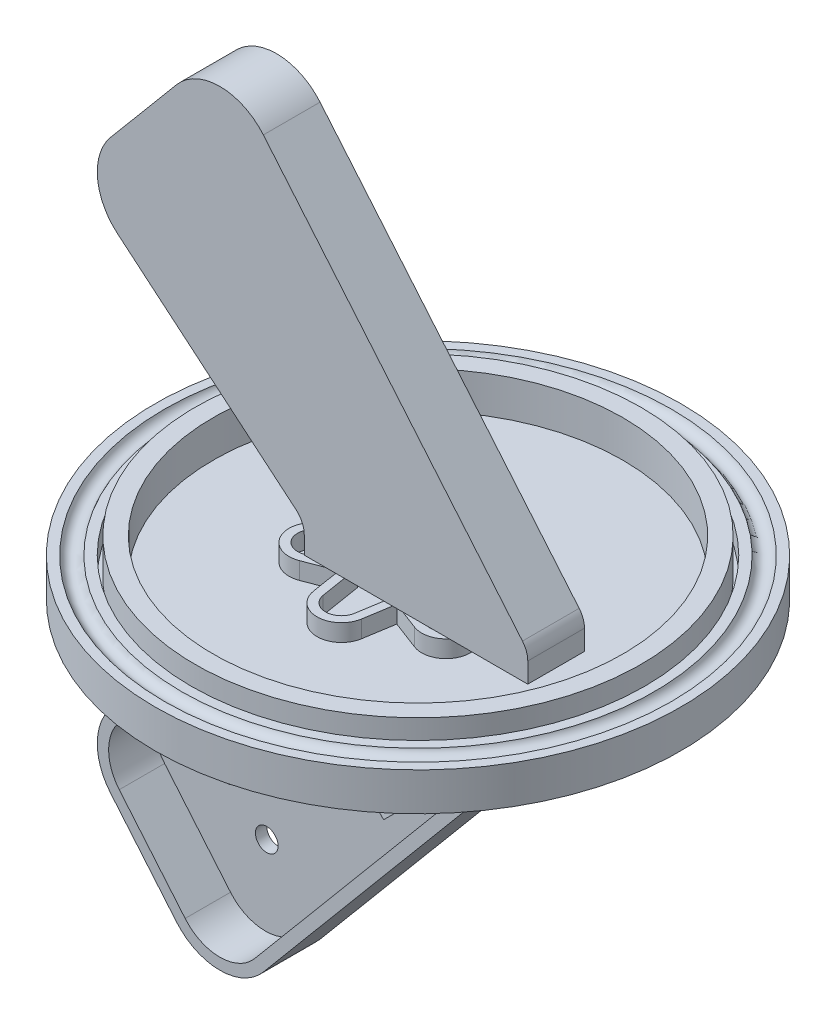
SolidWorks part; units mm, degrees
ref_plane "Front Plane" through (0, 0, 0) normal (0, 0, 1) x (1, 0, 0)
ref_plane "Top Plane" through (0, 0, 0) normal (0, 1, 0) x (1, 0, 0)
ref_plane "Right Plane" through (0, 0, 0) normal (1, 0, 0) x (0, 0, -1)
sketch "Sketch1" plane through (0, 0, 0) normal (0, 1, 0) x (1, 0, 0)
  circle A0 centre (0, 0) radius 82.55
  dimension "D1" = 165.1
extrude "Boss-Extrude1" add sketch "Sketch1" along normal blind 3.175 contours A0
sketch "Sketch3" plane through (0, 3.175, 0) normal (0, 1, 0) x (1, 0, 0)
  line L0 (0, 0) -> (-82.55, 0) construction
  circle A0 centre (0, 0) radius 82.55 construction
  circle A1 centre (-76.2, 0) radius 1.65
  dimension "D2" = 3.3
  dimension "D3" = 76.2
  dimension "D1" = 82.55
extrude "Cut-Extrude2" cut sketch "Sketch3" against normal blind 3.175
pattern_circular "CirPattern1" count 4 over 360 about axis through (0, 0, 0) along (0, 1, 0) of "Cut-Extrude2"
sketch "Sketch4" plane through (0, 3.175, 0) normal (0, 1, 0) x (1, 0, 0)
  line L0 (0, 0) -> (-9.65, 0) construction
  circle A0 centre (-9.65, 0) radius 40
  circle A1 centre (-9.65, 0) radius 46.35
  dimension "D2" = 6.35
  dimension "D3" = 80
  dimension "D1" = 9.65
extrude "Boss-Extrude2" add sketch "Sketch4" along normal blind 3.525
sketch "Sketch7" plane through (0, 0, 0) normal (0, 0, 1) x (1, 0, 0)
  line L1 (-9.65, 3.175) -> (-9.65, 34.2214) construction
  line L2 (82.55, 3.175) -> (-82.55, 3.175) construction
  circle A0 centre (-52.825, 7.2) radius 1.5875
  dimension "D1" = 3.175
  dimension "D2" = 52.825
  dimension "D3" = 4.025
revolve "Cut-Revolve1" cut sketch "Sketch7" angle 360 about L1
sketch "Sketch8" plane through (0, 3.175, 0) normal (0, 1, 0) x (1, 0, 0)
  circle A0 centre (-9.65, 0) radius 46.35
  circle A1 centre (-9.65, 0) radius 111.4897
extrude "Cut-Extrude3" cut sketch "Sketch8" against normal blind 10
sketch "Sketch12" plane through (0, 0, 0) normal (0, 0, 1) x (1, 0, 0)
  line L0 (-19.7064, 6.7) -> (-19.7064, 9.8348)
  line L1 (36.7, 6.7) -> (-56, 6.7) construction
  line L2 (-21.1352, 12.8989) -> (-52.6332, 39.3289)
  line L3 (-53.8657, 53.4172) -> (-42.2426, 67.2691)
  line L4 (-26.9217, 67.2691) -> (18.7706, 12.8153)
  line L5 (19.7064, 10.2441) -> (19.7064, 6.7)
  line L6 (-19.7064, 6.7) -> (19.7064, 6.7)
  line L7 (-56, 0) -> (36.7, 0) construction
  line L8 (0, 0) -> (0, 6.7) construction
  line L9 (30.35, 6.7) -> (-49.65, 6.7) construction
  line L10 (-19.7064, 11.7) -> (19.7064, 11.7) construction
  line L11 (-19.7064, 11.7) -> (19.7064, 6.7) construction
  line L12 (-19.7064, 6.7) -> (19.7064, 11.7) construction
  line L13 (0, 6.7) -> (0, 9.2) construction
  line L14 (-56, 0) -> (-56, 6.7) construction
  arc A0 (-52.6332, 39.3289) -> (-53.8657, 53.4172) centre (-46.2053, 46.9893) cw
  arc A1 (-42.2426, 67.2691) -> (-26.9217, 67.2691) centre (-34.5821, 60.8413) cw
  arc A2 (18.7706, 12.8153) -> (19.7064, 10.2441) centre (15.7064, 10.2441) cw
  arc A3 (-19.7064, 9.8348) -> (-21.1352, 12.8989) centre (-23.7064, 9.8348) ccw
  point P19 (-60.2936, 45.7567)
  point P22 (-34.5821, 76.3985)
  dimension "D6" = 10
  dimension "D7" = 4
  dimension "D1" = 40
  dimension "D2" = 50
  dimension "D3" = 40
  dimension "D4" = 80
  dimension "D5" = 5
extrude "Boss-Extrude4" add sketch "Sketch12" along normal blind 10 separate body contours L4 A2 L5 L6 L0 A3 L2 A0 L3 A1
ref_plane "Plane1" through (0, 3.35, 0) normal (0, 1, 0) x (1, 0, 0)
mirror "Mirror3" about plane through (0, 3.35, 0) normal (0, 1, 0) of "Boss-Extrude4"
sketch "Sketch13" plane through (0, 0, 10) normal (0, 0, 1) x (1, 0, 0)
  line L12 (-28.4538, -59.2836) -> (17.2385, -4.8297)
  line L13 (17.7064, -3.5441) -> (17.7064, -2)
  line L14 (17.7064, -2) -> (-17.7064, -2)
  line L15 (-17.7064, -2) -> (-17.7064, -3.1348)
  line L16 (-19.8497, -7.731) -> (-51.3476, -34.1609)
  line L17 (-52.3337, -45.4316) -> (-40.7105, -59.2836)
  line L18 (-28.4538, -59.2836) -> (17.2385, -4.8297)
  line L19 (17.7064, -3.5441) -> (17.7064, -2)
  line L20 (17.7064, -2) -> (-17.7064, -2)
  line L21 (-17.7064, -2) -> (-17.7064, -3.1348)
  line L22 (-19.8497, -7.731) -> (-51.3476, -34.1609)
  line L23 (-52.3337, -45.4316) -> (-40.7105, -59.2836)
  arc A8 (-40.7105, -59.2836) -> (-28.4538, -59.2836) centre (-34.5821, -54.1413) ccw
  arc A9 (17.2385, -4.8297) -> (17.7064, -3.5441) centre (15.7064, -3.5441) ccw
  arc A10 (-19.8497, -7.731) -> (-17.7064, -3.1348) centre (-23.7064, -3.1348) ccw
  arc A11 (-51.3476, -34.1609) -> (-52.3337, -45.4316) centre (-46.2053, -40.2893) ccw
  arc A12 (-40.7105, -59.2836) -> (-28.4538, -59.2836) centre (-34.5821, -54.1413) ccw
  arc A13 (17.2385, -4.8297) -> (17.7064, -3.5441) centre (15.7064, -3.5441) ccw
  arc A14 (-19.8497, -7.731) -> (-17.7064, -3.1348) centre (-23.7064, -3.1348) ccw
  arc A15 (-51.3476, -34.1609) -> (-52.3337, -45.4316) centre (-46.2053, -40.2893) ccw
  dimension "D1" = 2
extrude "Cut-Extrude4" cut sketch "Sketch13" against normal offset from surface (8 mm away) 2 up to face at (-18.0379, -22.3035, 0)
sketch "Sketch14" plane through (0, 0, 2) normal (0, 0, 1) x (1, 0, 0)
  line L0 (-42.2028, -34.4964) -> (-13.7064, -6) construction
  line L1 (-13.7064, -6) -> (0.6479, -20.3543)
  line L2 (0.6479, -20.3543) -> (-27.8485, -48.8507) construction
  line L3 (-27.8485, -48.8507) -> (-42.2028, -34.4964) construction
  line L4 (-56, 0) -> (36.7, 0) construction
  line L5 (17.7064, -2) -> (-17.7064, -2) construction
  line L7 (-19.7064, 0) -> (-19.7064, -3.1348) construction
  line L8 (-41.3896, -40.9664) -> (-7.2364, -6.8132) construction
  line L9 (-7.2364, -6.8132) -> (-0.1653, -13.8842) construction
  line L10 (-0.1653, -13.8842) -> (-34.3185, -48.0375) construction
  line L11 (-34.3185, -48.0375) -> (-41.3896, -40.9664) construction
  line L12 (-37.8541, -44.502) -> (-35.0257, -41.6735) construction
  line L13 (-24.313, -23.8898) -> (-27.9546, -20.2482) construction
  line L14 (-28.0607, -20.3543) -> (-13.7064, -34.7085)
  line L15 (-13.7064, -34.7085) -> (0.6479, -20.3543)
  line L16 (-13.7064, -6) -> (-28.0607, -20.3543)
  circle A0 centre (-7.2364, -6.8132) radius 2
  circle A1 centre (-0.1653, -13.8842) radius 2
  circle A2 centre (-41.3896, -40.9664) radius 2
  circle A3 centre (-34.3185, -48.0375) radius 2
  dimension "D6" = 4
  dimension "D1" = 45
  dimension "D2" = 4
  dimension "D3" = 40.3
  dimension "D4" = 20.3
  dimension "D5" = 6
  dimension "D7" = 10
  dimension "D8" = 48.3
  dimension "D9" = 20
extrude "Cut-Extrude5" cut sketch "Sketch14" against normal up to next (2 mm away)
sketch "Sketch15" plane through (0, 3.175, 0) normal (0, 1, 0) x (1, 0, 0)
  line L18 (-20.3443, -9.3665) -> (-13.5666, -6.7837)
  line L20 (-13.5666, -6.7837) -> (-12.4145, -13.9448)
  line L21 (-6.8855, -13.9448) -> (-5.7334, -6.7837)
  line L23 (-5.7334, -6.7837) -> (1.0443, -9.3665)
  line L24 (3.8087, -4.5783) -> (-1.8169, 0)
  line L26 (-1.8169, 0) -> (3.8087, 4.5783)
  line L27 (1.0443, 9.3665) -> (-5.7334, 6.7837)
  line L29 (-5.7334, 6.7837) -> (-6.8855, 13.9448)
  line L30 (-12.4145, 13.9448) -> (-13.5666, 6.7837)
  line L32 (-13.5666, 6.7837) -> (-20.3443, 9.3665)
  line L33 (-23.1087, 4.5783) -> (-17.4831, 0)
  line L35 (-17.4831, 0) -> (-23.1087, -4.5783)
  line L36 (-19.8102, -10.7681) -> (-14.7548, -8.8417)
  line L37 (-14.7548, -8.8417) -> (-13.8954, -14.183)
  line L38 (-5.4046, -14.183) -> (-4.5452, -8.8417)
  line L39 (-4.5452, -8.8417) -> (0.5102, -10.7681)
  line L40 (4.7556, -3.4149) -> (0.5595, 0)
  line L41 (0.5595, 0) -> (4.7556, 3.4149)
  line L42 (0.5102, 10.7681) -> (-4.5452, 8.8417)
  line L43 (-4.5452, 8.8417) -> (-5.4046, 14.183)
  line L44 (-13.8954, 14.183) -> (-14.7548, 8.8417)
  line L45 (-14.7548, 8.8417) -> (-19.8102, 10.7681)
  line L46 (-24.0556, 3.4149) -> (-19.8595, 0)
  line L47 (-19.8595, 0) -> (-24.0556, -3.4149)
  circle A0 centre (-9.65, 0) radius 39.5
  circle A1 centre (-9.65, 0) radius 36.325
  circle A2 centre (-9.65, 0) radius 40 construction
  arc A10 (-12.4145, -13.9448) -> (-6.8855, -13.9448) centre (-9.65, -13.5) ccw
  arc A11 (1.0443, -9.3665) -> (3.8087, -4.5783) centre (2.0413, -6.75) ccw
  arc A12 (3.8087, 4.5783) -> (1.0443, 9.3665) centre (2.0413, 6.75) ccw
  arc A13 (-6.8855, 13.9448) -> (-12.4145, 13.9448) centre (-9.65, 13.5) ccw
  arc A14 (-20.3443, 9.3665) -> (-23.1087, 4.5783) centre (-21.3413, 6.75) ccw
  arc A15 (-23.1087, -4.5783) -> (-20.3443, -9.3665) centre (-21.3413, -6.75) ccw
  arc A23 (-13.8954, -14.183) -> (-5.4046, -14.183) centre (-9.65, -13.5) ccw
  arc A24 (0.5102, -10.7681) -> (4.7556, -3.4149) centre (2.0413, -6.75) ccw
  arc A25 (4.7556, 3.4149) -> (0.5102, 10.7681) centre (2.0413, 6.75) ccw
  arc A26 (-5.4046, 14.183) -> (-13.8954, 14.183) centre (-9.65, 13.5) ccw
  arc A27 (-19.8102, 10.7681) -> (-24.0556, 3.4149) centre (-21.3413, 6.75) ccw
  arc A28 (-24.0556, -3.4149) -> (-19.8102, -10.7681) centre (-21.3413, -6.75) ccw
  dimension "D1" = 0.5
  dimension "D2" = 3.175
  dimension "D3" = 1.5
extrude "Boss-Extrude5" add sketch "Sketch15" along normal blind 3.025 contours L47 A28 L36 L37 A23 L38 L39 A24 L40 L41 A25 L42 L43 A26 L44 L45 A27 L46 A15 L35 L33 A14 L32 L30 A13 L29 L27 A12 L26 L24 A11 L23 L21 A10 L20 L18
sketch "Sketch16" plane through (0, 3.175, 0) normal (0, 1, 0) x (1, 0, 0)
  circle A0 centre (-9.65, 0) radius 39.3
  circle A1 centre (-9.65, 0) radius 36.125
  circle A2 centre (-9.65, 0) radius 40 construction
  dimension "D1" = 3.175
  dimension "D2" = 0.7
extrude "Boss-Extrude6" add sketch "Sketch16" along normal blind 6.5
